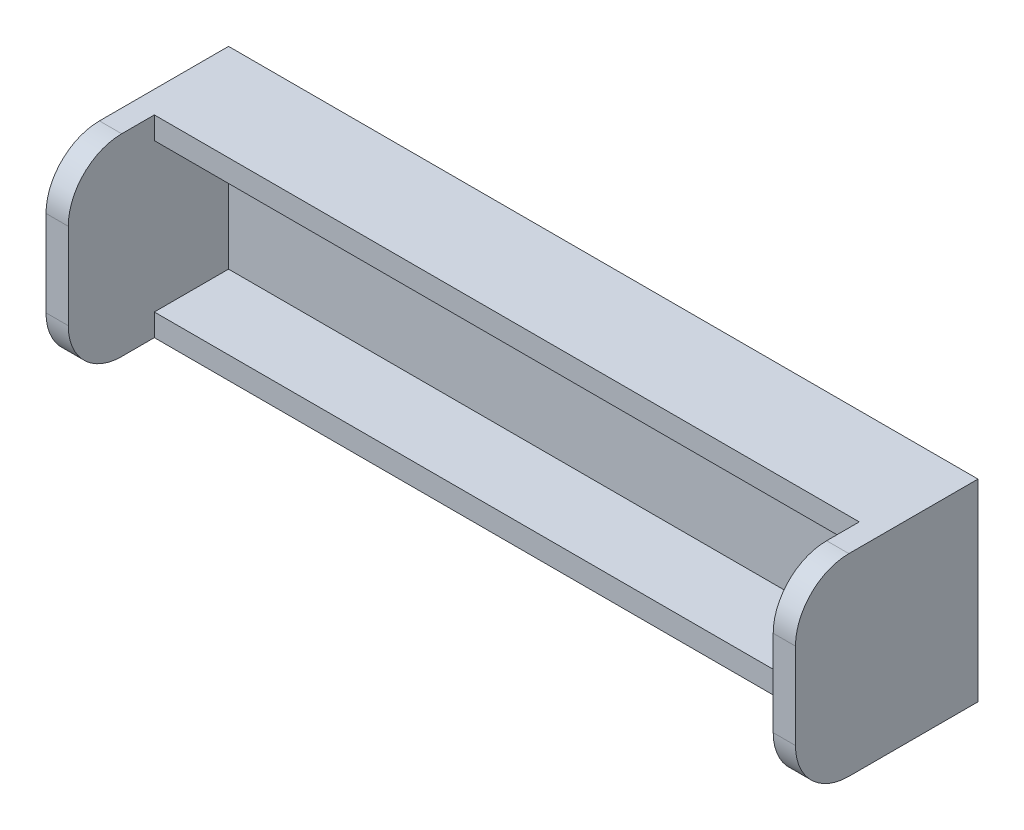
SolidWorks part; units mm, degrees
ref_plane "Front Plane" through (0, 0, 0) normal (0, 0, 1) x (1, 0, 0)
ref_plane "Top Plane" through (0, 0, 0) normal (0, 1, 0) x (1, 0, 0)
ref_plane "Right Plane" through (0, 0, 0) normal (1, 0, 0) x (0, 0, -1)
sketch "Sketch1" plane through (0, 0, 0) normal (1, 0, 0) x (0, 0, -1)
  line L0 (0, 6.5) -> (0, -6.5)
  line L1 (0, 6.5) -> (-8.7, 6.5)
  line L2 (0, 0) -> (-12.3, 0) construction
  line L3 (-12.3, -2.9) -> (-12.3, 2.9)
  line L4 (0, -6.5) -> (-8.7, -6.5)
  arc A0 (-8.7, 6.5) -> (-12.3, 2.9) centre (-8.7, 2.9) ccw
  arc A1 (-8.7, -6.5) -> (-12.3, -2.9) centre (-8.7, -2.9) cw
  dimension "D1" = 13
  dimension "D2" = 12.3
  dimension "D3" = 3.6
extrude "Boss-Extrude1" add sketch "Sketch1" along normal blind 1.5
pattern_linear "LPattern1" count 2 spacing 49 along (1, 0, 0) of "Boss-Extrude1"
sketch "Sketch2" plane through (0, 0, 0) normal (0, 0, 1) x (1, 0, 0)
  line L0 (1.5, -6.5) -> (0, -6.5) construction
  line L1 (0, 6.5) -> (50.5, 6.5)
  line L2 (0, 6.5) -> (0, -6.5)
  line L3 (0, -6.5) -> (50.5, -6.5)
  line L4 (50.5, 6.5) -> (50.5, -6.5)
  line L5 (50.5, 2.9) -> (50.5, -2.9) construction
extrude "Boss-Extrude2" add sketch "Sketch2" along normal blind 1.5
sketch "Sketch3" plane through (0, -6.5, 0) normal (0, -1, 0) x (1, 0, 0)
  line L0 (0, 8.7) -> (0, 0) construction
  line L1 (0, 6.5) -> (50.5, 6.5)
  line L2 (0, 6.5) -> (0, 0)
  line L3 (0, 0) -> (50.5, 0)
  line L4 (50.5, 6.5) -> (50.5, 0)
  dimension "D1" = 6.5
extrude "Boss-Extrude3" add sketch "Sketch3" against normal blind 1.5
mirror "Mirror1" about plane through (0, 0, 0) normal (0, 1, 0) of "Boss-Extrude3"
sketch "Sketch4" plane through (0, 0, 0) normal (0, 0, -1) x (-1, 0, 0)
  line L0 (-25.25, 6.5) -> (-25.25, -6.5) construction
  line L1 (-50.5, 6.5) -> (0, 6.5) construction
  line L2 (-50.5, -6.5) -> (0, -6.5) construction
ref_plane "Plane1" through (25.25, 0, 0) normal (1, 0, 0) x (0, -1, 0)
